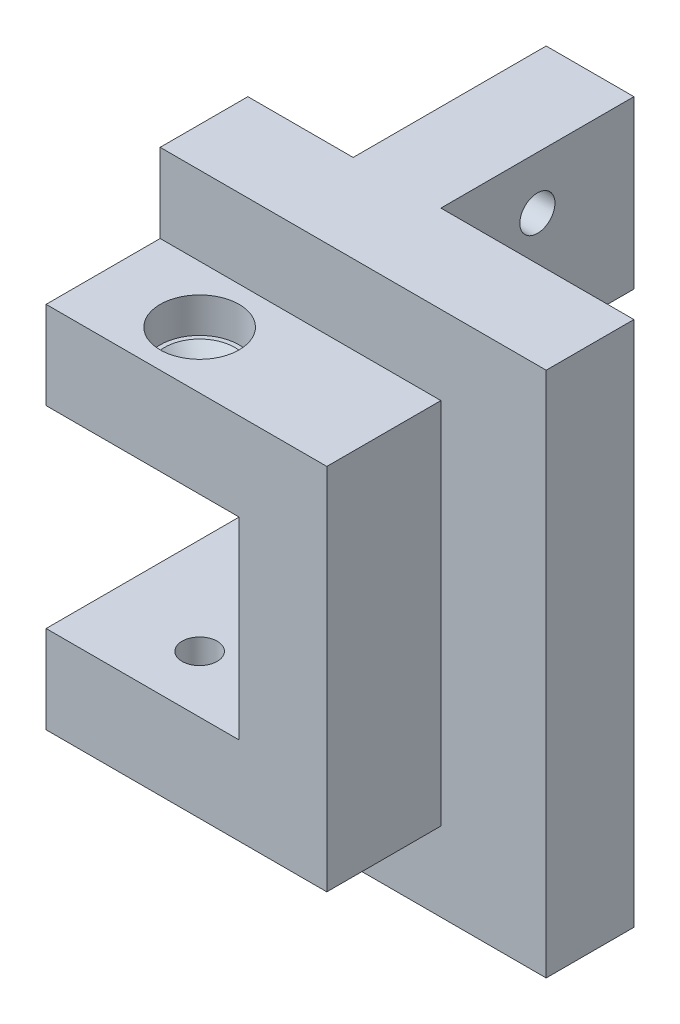
SolidWorks part; units mm, degrees
ref_plane "Top Plane" through (0, 0, 0) normal (0, 0, 1) x (1, 0, 0)
ref_plane "Right Plane" through (0, 0, 0) normal (0, 1, 0) x (1, 0, 0)
ref_plane "Front Plane" through (0, 0, 0) normal (1, 0, 0) x (0, 0, -1)
sketch "Sketch1" plane through (0, 0, 0) normal (0, 0, 1) x (1, 0, 0)
  line L2 (0, 0) -> (0, -30)
  line L3 (0, -30) -> (-44, -30)
  line L4 (-22, 0) -> (-22, -11)
  line L13 (-22, -11) -> (-44, -11)
  line L14 (-44, -30) -> (-44, -11)
  line L15 (-22, -86) -> (-22, 64) construction
  line L16 (0, 0) -> (-22, 0)
  line L18 (0, -86) -> (0, 64) construction
  line L19 (0, -71.7291) -> (0, -30)
  dimension "D1" = 30
  dimension "D2" = 11
extrude "Boss-Extrude1" add sketch "Sketch1" along normal blind 10
sketch "Sketch2" plane through (0, 0, 10) normal (0, 0, 1) x (1, 0, 0)
  line L0 (-22, -11) -> (-44, -11) construction
  line L1 (-44, -11) -> (-22, -11)
  line L2 (-44, -11) -> (-44, -18)
  line L3 (-44, -18) -> (-32, -18)
  line L5 (0, -30) -> (-44, -30) construction
  line L7 (-22, -11) -> (-22, -30)
  line L8 (-22, -30) -> (-32, -30)
  line L9 (-32, -18) -> (-32, -30)
  dimension "D1" = 7
  dimension "D2" = 10
extrude "Boss-Extrude2" add sketch "Sketch2" against normal offset from surface (32 mm away) 22 up to face at (-22, -13.6667, 0) offset beyond the face yes
sketch "Sketch3" plane through (0, 0, 10) normal (0, 0, 1) x (1, 0, 0)
  line L1 (-44, -11) -> (-22, -11)
  line L2 (-44, -11) -> (-44, -21)
  line L3 (-44, -21) -> (-12, -21)
  line L6 (-12, -21) -> (-12, 0)
  line L7 (-12, 0) -> (-22, 0)
  line L8 (-22, -11) -> (-22, 0)
  point P9 (-12, -20.5161)
  dimension "D1" = 10
  dimension "D2" = 10
extrude "Boss-Extrude3" add sketch "Sketch3" along normal blind 13
sketch "Sketch4" plane through (0, -21, 0) normal (0, -1, 0) x (1, 0, 0)
  line L0 (-44, 16.5) -> (-33, 16.5) construction
  line L1 (-44, 23) -> (-44, 10) construction
  circle A0 centre (-33, 16.5) radius 2
  dimension "D1" = 4
  dimension "D2" = 11
extrude "Cut-Extrude1" cut sketch "Sketch4" against normal through all
sketch "Sketch5" plane through (-32, 0, 0) normal (-1, 0, 0) x (0, 0, 1)
  line L0 (-11, -24) -> (-22, -24) construction
  line L1 (-22, -30) -> (-22, -18) construction
  circle A0 centre (-11, -24) radius 2
  dimension "D1" = 4
  dimension "D2" = 11
extrude "Cut-Extrude2" cut sketch "Sketch5" against normal through all
sketch "Sketch6" plane through (-32, 0, 0) normal (-1, 0, 0) x (0, 0, 1)
  circle A0 centre (-11, -24) radius 4.5
  dimension "D1" = 9
extrude "Cut-Extrude3" cut sketch "Sketch6" against normal offset from surface (4 mm away) 6 up to face at (-22, -22, -11)
sketch "Sketch7" plane through (0, -21, 0) normal (0, -1, 0) x (1, 0, 0)
  circle A0 centre (-33, 16.5) radius 4.5
  dimension "D1" = 9
extrude "Cut-Extrude4" cut sketch "Sketch7" against normal offset from surface (4 mm away) 6 up to face at (-31, -11, 16.5)
chamfer "Chamfer2" distance 2 angle 45 2 edges at (-31, -17, 16.5) (-28, -22, -11)
mirror "Mirror1" about plane through (0, 0, 10) normal (0, -1, 0) of bodies 109 106
